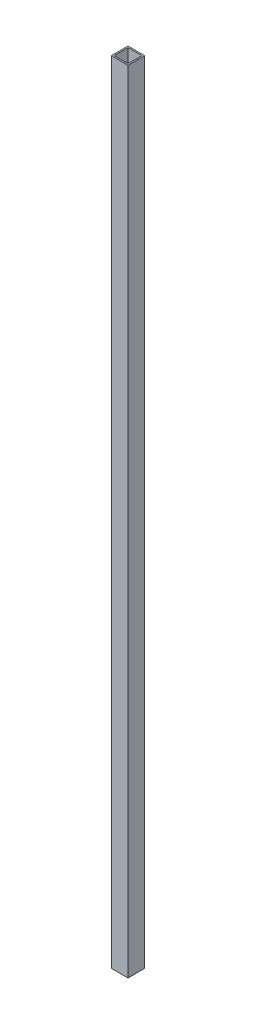
SolidWorks part; units mm, degrees
ref_plane "Front" through (0, 0, 0) normal (0, 0, 1) x (1, 0, 0)
ref_plane "Top" through (0, 0, 0) normal (0, 1, 0) x (1, 0, 0)
ref_plane "Right" through (0, 0, 0) normal (1, 0, 0) x (0, 0, -1)
sketch "Sketch1" plane through (0, 0, 0) normal (0, 1, 0) x (1, 0, 0)
  line L1 (0, 0) -> (19.05, 0)
  line L2 (0, 0) -> (0, 19.05)
  line L3 (0, 19.05) -> (19.05, 19.05)
  line L4 (19.05, 0) -> (19.05, 19.05)
  line L5 (0, 0) -> (19.05, 19.05) construction
  line L6 (0, 19.05) -> (19.05, 0) construction
  line L7 (1.5875, 1.5875) -> (17.4625, 1.5875)
  line L8 (1.5875, 1.5875) -> (1.5875, 17.4625)
  line L9 (1.5875, 17.4625) -> (17.4625, 17.4625)
  line L10 (17.4625, 1.5875) -> (17.4625, 17.4625)
  line L11 (1.5875, 1.5875) -> (17.4625, 17.4625) construction
  line L12 (1.5875, 17.4625) -> (17.4625, 1.5875) construction
  point P4 (9.525, 9.525)
  point P5 (9.525, 9.525)
  dimension "D1" = 1.5875
  dimension "D2" = 1.5875
  dimension "D3" = 19.05
extrude "Boss-Extrude1" add sketch "Sketch1" along normal blind 901.7
